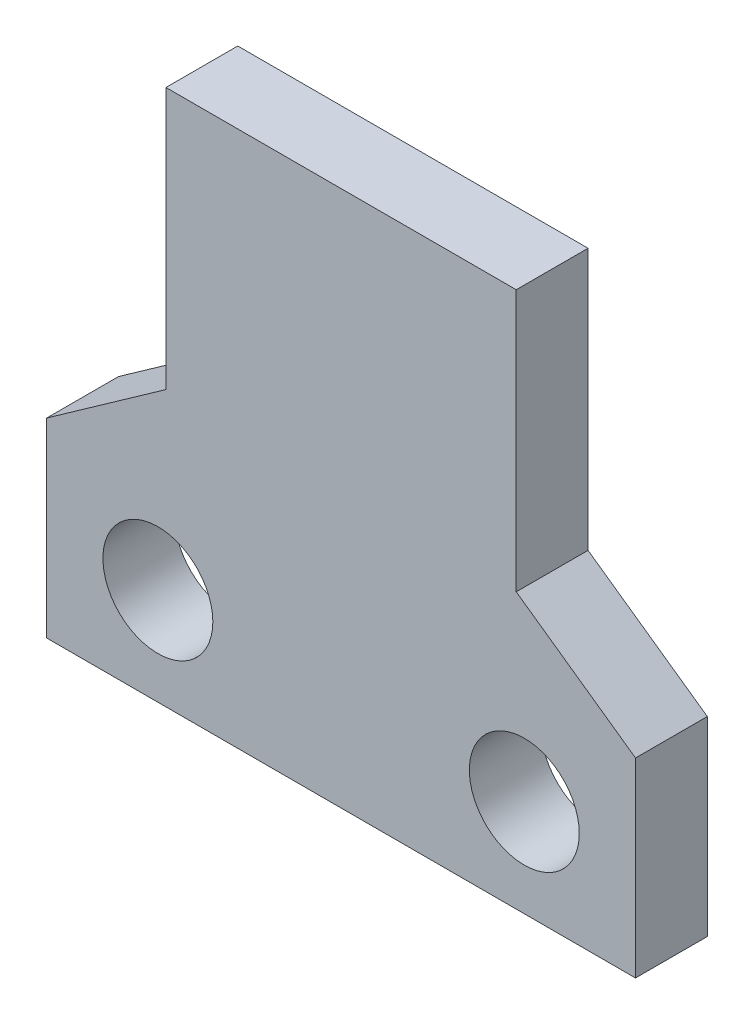
SolidWorks part; units mm, degrees
ref_plane "Piano frontale" through (0, 0, 0) normal (0, 0, 1) x (1, 0, 0)
ref_plane "Piano superiore" through (0, 0, 0) normal (0, 1, 0) x (1, 0, 0)
ref_plane "Piano destro" through (0, 0, 0) normal (1, 0, 0) x (0, 0, -1)
sketch "Schizzo1" plane through (0, 0, 0) normal (0, 0, 1) x (1, 0, 0)
  line L1 (-8.035, -7.32) -> (8.035, -7.32)
  line L2 (-8.035, -7.32) -> (-8.035, 7.32)
  line L3 (-8.035, 7.32) -> (8.035, 7.32)
  line L4 (8.035, -7.32) -> (8.035, 7.32)
  line L5 (-8.035, -7.32) -> (8.035, 7.32) construction
  line L6 (-8.035, 7.32) -> (8.035, -7.32) construction
  point P0 (0, 0)
  dimension "D1" = 16.07
  dimension "D2" = 14.64
extrude "Estrusione-Estrusione1" add sketch "Schizzo1" against normal blind 1.96
sketch "Schizzo2" plane through (0, 0, 0) normal (0, 0, 1) x (1, 0, 0)
  line L0 (0, 7.32) -> (0, -7.32) construction
  line L1 (-4.78, 7.32) -> (-4.78, 0.18)
  line L2 (-4.78, 0.18) -> (-8.035, -2.12)
  line L3 (4.78, 0.18) -> (8.035, -2.12)
  line L4 (8.035, -7.32) -> (8.035, 7.32)
  line L5 (8.035, 7.32) -> (-8.035, 7.32)
  line L6 (-8.035, 7.32) -> (-8.035, -7.32)
  line L7 (-8.035, -7.32) -> (8.035, -7.32)
  line L8 (8.035, -7.32) -> (8.035, 7.32)
  line L9 (8.035, 7.32) -> (-8.035, 7.32)
  line L10 (-8.035, 7.32) -> (-8.035, -7.32)
  line L11 (-8.035, -7.32) -> (8.035, -7.32)
  line L12 (4.78, 7.32) -> (4.78, 0.18)
  line M5 (8.035, -7.32) -> (8.035, 7.32)
  line M6 (8.035, 7.32) -> (-8.035, 7.32)
  line M7 (-8.035, 7.32) -> (-8.035, -7.32)
  dimension "D2" = 9.56
  dimension "D3" = 7.5
  dimension "D4" = 5.2
  dimension "D1" = 0
extrude "Taglio-Estrusione1" cut sketch "Schizzo2" against normal through all contours L2 L1 M6 M7 | L12 L3 M6 M5
sketch "Schizzo3" plane through (0, 0, 0) normal (0, 0, 1) x (1, 0, 0)
  line L0 (-5, -4.67) -> (5, -4.67) construction
  line L1 (0, 0) -> (0, -4.67) construction
  line L2 (-8.035, -7.32) -> (8.035, -7.32) construction
  circle A0 centre (-5, -4.67) radius 1.5
  circle A1 centre (5, -4.67) radius 1.5
  dimension "D1" = 3
  dimension "D2" = 10
  dimension "D3" = 2.65
extrude "Taglio-Estrusione2" cut sketch "Schizzo3" against normal through all
